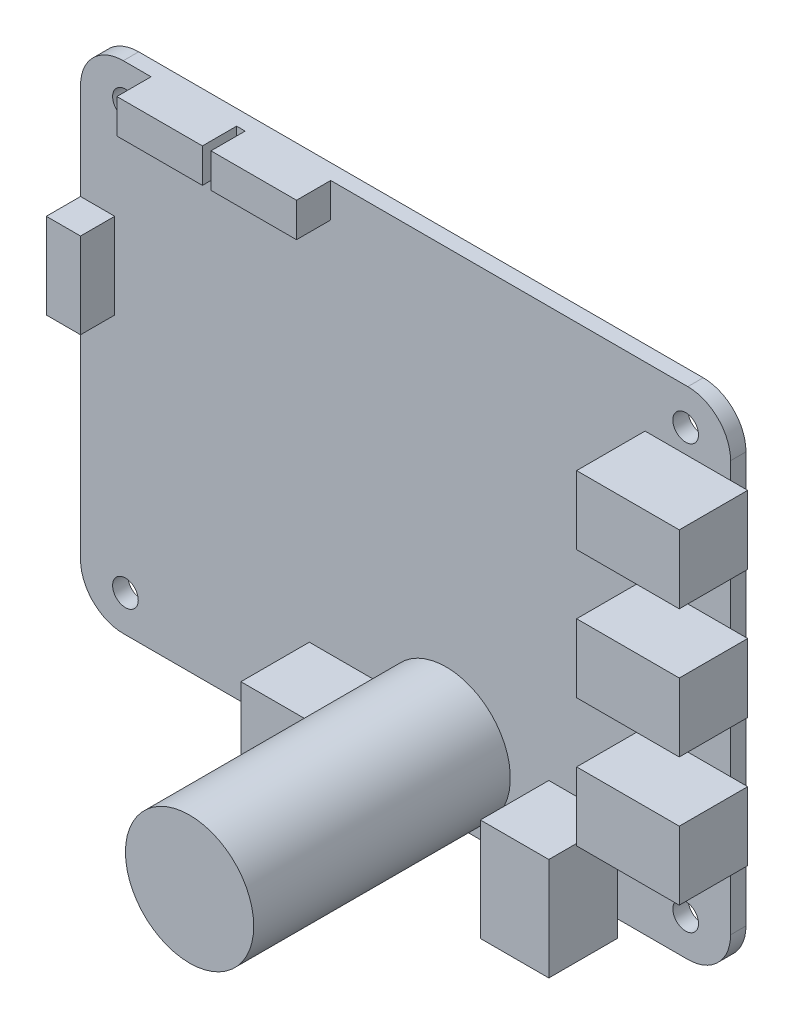
SolidWorks part; units mm, degrees
material "A-玻璃纤维"
ref_plane "前视基准面" through (0, 0, 0) normal (0, 0, 1) x (1, 0, 0)
ref_plane "上视基准面" through (0, 0, 0) normal (0, 1, 0) x (1, 0, 0)
ref_plane "右视基准面" through (0, 0, 0) normal (1, 0, 0) x (0, 0, -1)
sketch "草图1" plane through (0, 0, 0) normal (0, 0, 1) x (1, 0, 0)
  line L1 (-38, -29) -> (38, -29)
  line L2 (-38, -29) -> (-38, 29)
  line L3 (-38, 29) -> (38, 29)
  line L4 (38, -29) -> (38, 29)
  line L5 (-38, -29) -> (38, 29) construction
  line L6 (-38, 29) -> (38, -29) construction
  line L7 (-32.75, -24.75) -> (32.75, -24.75) construction
  line L8 (-32.75, -24.75) -> (-32.75, 24.75) construction
  line L9 (-32.75, 24.75) -> (32.75, 24.75) construction
  line L10 (32.75, -24.75) -> (32.75, 24.75) construction
  line L11 (-32.75, -24.75) -> (32.75, 24.75) construction
  line L12 (-32.75, 24.75) -> (32.75, -24.75) construction
  circle A0 centre (-32.75, 24.75) radius 1.5
  circle A1 centre (-32.75, -24.75) radius 1.5
  circle A2 centre (32.75, -24.75) radius 1.5
  circle A3 centre (32.75, 24.75) radius 1.5
  point P0 (0, 0)
  point P6 (0, 0)
  dimension "D5" = 3
  dimension "D1" = 76
  dimension "D2" = 58
  dimension "D3" = 49.5
  dimension "D4" = 65.5
extrude "凸台-拉伸1" add sketch "草图1" along normal blind 1.8
sketch "草图2" plane through (0, 0, 1.8) normal (0, 0, 1) x (1, 0, 0)
  line L0 (38, -29) -> (38, 29) construction
  line L1 (28, 22) -> (40, 22)
  line L2 (28, 22) -> (28, 14)
  line L3 (28, 14) -> (40, 14)
  line L4 (40, 22) -> (40, 14)
  line L5 (38, 29) -> (-38, 29) construction
  line L6 (28, 7) -> (28, -1)
  line L7 (28, 7) -> (40, 7)
  line L8 (40, 7) -> (40, -1)
  line L9 (28, -1) -> (40, -1)
  line L10 (28, -8) -> (28, -16)
  line L11 (28, -8) -> (40, -8)
  line L12 (40, -8) -> (40, -16)
  line L13 (28, -16) -> (40, -16)
  line L14 (-38, -29) -> (38, -29) construction
  line L15 (-11.25, -19) -> (-3.25, -19)
  line L16 (-11.25, -19) -> (-11.25, -31)
  line L17 (-11.25, -31) -> (-3.25, -31)
  line L18 (-3.25, -19) -> (-3.25, -31)
  line L19 (16.75, -19) -> (24.75, -19)
  line L20 (16.75, -19) -> (16.75, -31)
  line L21 (16.75, -31) -> (24.75, -31)
  line L22 (24.75, -19) -> (24.75, -31)
  circle A0 centre (32.75, -24.75) radius 1.5 construction
  dimension "D1" = 2
  dimension "D2" = 8
  dimension "D3" = 12
  dimension "D4" = 7
  dimension "D6" = 15
  dimension "D7" = 2
  dimension "D8" = 2
  dimension "D9" = 8
  dimension "D10" = 8
  dimension "D11" = 12
  dimension "D12" = 12
  dimension "D13" = 8
  dimension "D14" = 20
  dimension "D5" = 3
extrude "凸台-拉伸2" add sketch "草图2" along normal blind 8
sketch "草图3" plane through (0, 0, 1.8) normal (0, 0, 1) x (1, 0, 0)
  line L0 (38, 29) -> (-38, 29) construction
  line L1 (-29.75, 29) -> (-19.75, 29)
  line L2 (-29.75, 29) -> (-29.75, 25)
  line L3 (-29.75, 25) -> (-19.75, 25)
  line L4 (-19.75, 29) -> (-19.75, 25)
  line L5 (-38, 29) -> (-38, -29) construction
  line L6 (-18.75, 29) -> (-8.75, 29)
  line L7 (-18.75, 29) -> (-18.75, 25)
  line L8 (-18.75, 25) -> (-8.75, 25)
  line L9 (-8.75, 29) -> (-8.75, 25)
  line L10 (-38, 12.75) -> (-34, 12.75)
  line L11 (-38, 12.75) -> (-38, 2.75)
  line L12 (-38, 2.75) -> (-34, 2.75)
  line L13 (-34, 12.75) -> (-34, 2.75)
  circle A0 centre (-32.75, 24.75) radius 1.5 construction
  point P18 (-18.75, 27)
  dimension "D1" = 4
  dimension "D2" = 10
  dimension "D3" = 4
  dimension "D4" = 10
  dimension "D5" = 4
  dimension "D6" = 10
  dimension "D7" = 3
  dimension "D8" = 1
  dimension "D9" = 12
extrude "凸台-拉伸3" add sketch "草图3" along normal blind 4
sketch "草图4" plane through (0, 0, 1.8) normal (0, 0, 1) x (1, 0, 0)
  line L0 (-3.25, -29) -> (16.75, -29) construction
  line L1 (-3.25, -29) -> (-3.25, -19) construction
  circle A0 centre (4.75, -21) radius 7.5
  dimension "D1" = 15
  dimension "D2" = 8
  dimension "D3" = 8
extrude "凸台-拉伸4" add sketch "草图4" along normal blind 30
fillet "圆角1" radius 5 4 edges at (-38, 29, 0.9) (38, 29, 0.9) (38, -29, 0.9) (-38, -29, 0.9)
